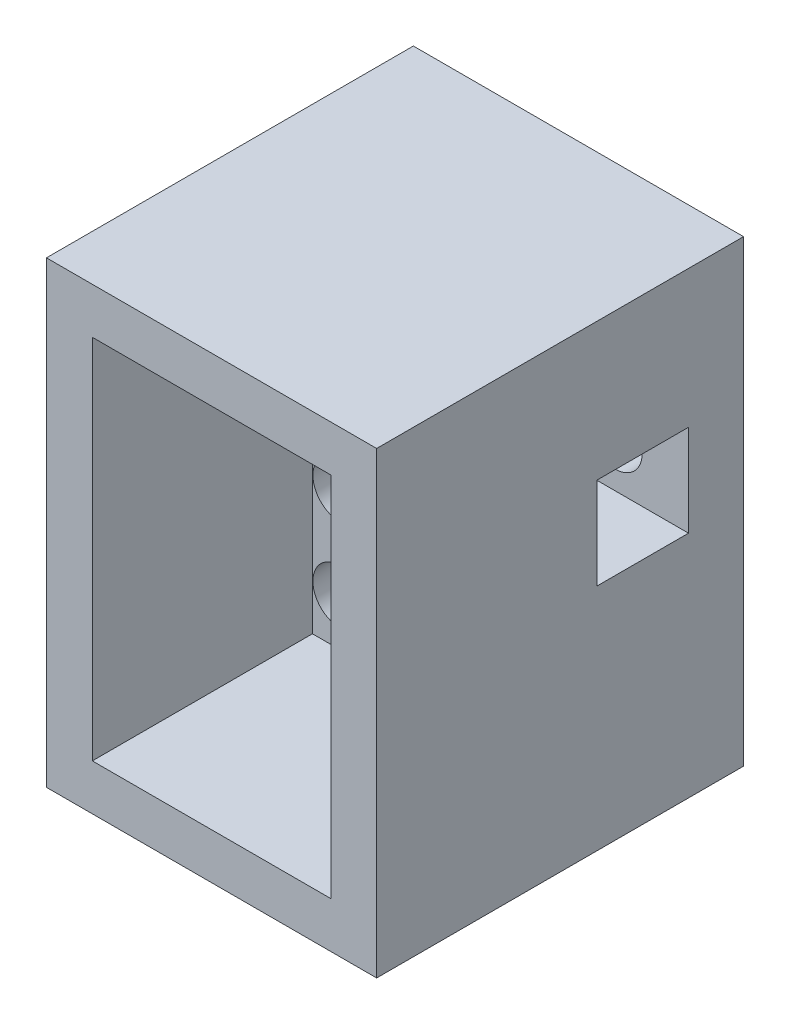
SolidWorks part; units mm, degrees
ref_plane "Front Plane" through (0, 0, 0) normal (1, 0, 0) x (0, 1, 0)
ref_plane "Top Plane" through (0, 0, 0) normal (0, 0, 1) x (0, 1, 0)
ref_plane "Right Plane" through (0, 0, 0) normal (0, 1, 0) x (-1, 0, 0)
sketch "Sketch1" plane through (0, 0, 0) normal (0, 0, 1) x (0, 1, 0)
  line L1 (-12.5, 9) -> (12.5, 9)
  line L2 (-12.5, 9) -> (-12.5, -9)
  line L3 (-12.5, -9) -> (12.5, -9)
  line L4 (12.5, 9) -> (12.5, -9)
  line L5 (-12.5, 9) -> (12.5, -9) construction
  line L6 (-12.5, -9) -> (12.5, 9) construction
  point P0 (0, 0)
  dimension "D1" = 18
  dimension "D2" = 25
extrude "Boss-Extrude1" add sketch "Sketch1" along normal blind 20
sketch "Sketch2" plane through (0, 0, 20) normal (0, 0, 1) x (1, 0, 0)
  line L1 (-6.5, 10) -> (6.5, 10)
  line L2 (-6.5, 10) -> (-6.5, -10)
  line L3 (-6.5, -10) -> (6.5, -10)
  line L4 (6.5, 10) -> (6.5, -10)
  line L5 (-6.5, 10) -> (6.5, -10) construction
  line L6 (-6.5, -10) -> (6.5, 10) construction
  point P0 (0, 0)
  dimension "D1" = 20
  dimension "D2" = 13
extrude "Cut-Extrude1" cut sketch "Sketch2" against normal blind 12
sketch "Sketch5" plane through (0, 0, 8) normal (0, 0, 1) x (1, 0, 0)
  line L0 (6.5, 10) -> (-6.5, 10) construction
  line L1 (-2.5, 10) -> (2.5, 10)
  line L2 (-2.5, 10) -> (-2.5, 0)
  line L3 (-2.5, 0) -> (2.5, 0)
  line L4 (2.5, 10) -> (2.5, 0)
  dimension "D1" = 5
extrude "Cut-Extrude4" cut sketch "Sketch5" against normal blind 8
sketch "Sketch3" plane through (0, 0, 0) normal (0, 0, -1) x (1, 0, 0)
  circle A0 centre (-5, 7.5) radius 1.475
  dimension "D1" = 2.95
  dimension "D2" = 5
  dimension "D3" = 7.5
extrude "Cut-Extrude2" cut sketch "Sketch3" against normal blind 10
pattern_linear "LPattern1" count 3 spacing 5 along (1, 0, 0) count 4 spacing 5 along (0, 1, 0) skipping (1, 2), (1, 3) of "Cut-Extrude2"
sketch "Sketch4" plane through (9, 0, 0) normal (1, 0, 0) x (0, 1, 0)
  line L1 (0, 3) -> (5, 3)
  line L2 (0, 3) -> (0, 8)
  line L3 (0, 8) -> (5, 8)
  line L4 (5, 3) -> (5, 8)
  dimension "D1" = 5
  dimension "D2" = 5
extrude "Cut-Extrude3" cut sketch "Sketch4" against normal up to surface (6.5 mm away) up to face at (2.5, 5, 4)
chamfer "Chamfer1" distance 2 angle 45 1 edges at (2.5, 5, 5.5)
